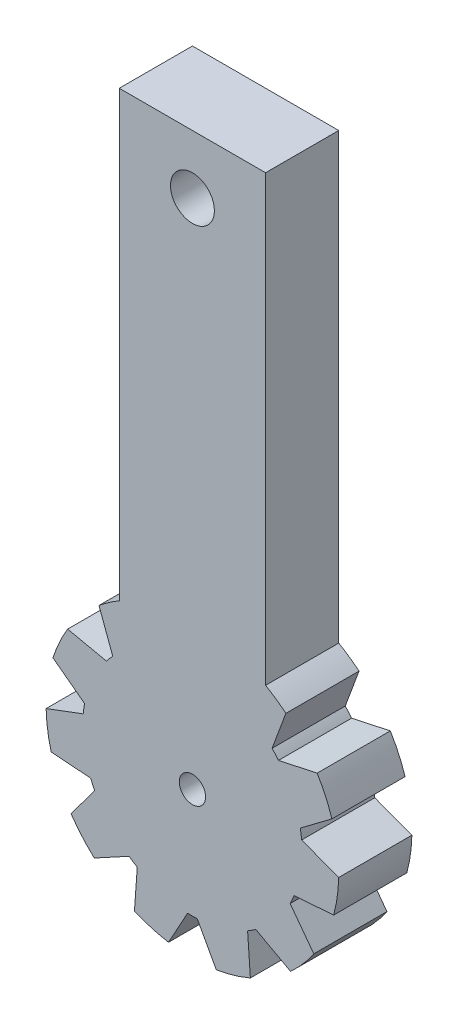
SolidWorks part; units mm, degrees
ref_plane "Front Plane" through (0, 0, 0) normal (0, 0, 1) x (1, 0, 0)
ref_plane "Top Plane" through (0, 0, 0) normal (0, 1, 0) x (1, 0, 0)
ref_plane "Right Plane" through (0, 0, 0) normal (1, 0, 0) x (0, 0, -1)
sketch "Sketch1" plane through (0, 0, 0) normal (0, 0, 1) x (1, 0, 0)
  line L0 (0, 11.2329) -> (0, -11.9005) construction
  line L1 (-1.7923, 7.2827) -> (-1.2129, 9.9262)
  line L2 (1.7923, 7.2827) -> (1.2129, 9.9262)
  line L3 (2.4295, 7.0956) -> (4.3461, 9.0062)
  line L4 (5.4451, 5.1576) -> (6.3869, 7.6947)
  line L5 (5.88, 4.6557) -> (8.5253, 5.2268)
  line L6 (7.3691, 1.395) -> (9.533, 3.0202)
  line L7 (7.4636, 0.7376) -> (9.9978, -0.2121)
  line L8 (6.9535, -2.8105) -> (9.6525, -2.6132)
  line L9 (6.6776, -3.4146) -> (8.296, -5.5836)
  line L10 (4.3302, -6.1237) -> (6.7074, -7.4169)
  line L11 (3.7715, -6.4827) -> (3.9603, -9.1824)
  line L12 (0.3321, -7.4926) -> (1.6327, -9.8658)
  line L13 (-0.3321, -7.4926) -> (-1.6327, -9.8658)
  line L14 (-3.7715, -6.4827) -> (-3.9603, -9.1824)
  line L15 (-4.3302, -6.1237) -> (-6.7074, -7.4169)
  line L16 (-6.6776, -3.4146) -> (-8.296, -5.5836)
  line L17 (-6.9535, -2.8105) -> (-9.6525, -2.6132)
  line L18 (-7.4636, 0.7376) -> (-9.9978, -0.2121)
  line L19 (-7.3691, 1.395) -> (-9.533, 3.0202)
  line L20 (-5.88, 4.6557) -> (-8.5253, 5.2268)
  line L21 (-5.4451, 5.1576) -> (-6.3869, 7.6947)
  line L22 (-2.4295, 7.0956) -> (-4.3461, 9.0062)
  arc A0 (-5.4451, 5.1576) -> (-5.88, 4.6557) centre (0, 0) ccw
  circle A1 centre (0, 0) radius 8.7846 construction
  arc A2 (1.2129, 9.9262) -> (-1.2129, 9.9262) centre (0, 0) ccw
  arc A3 (6.3869, 7.6947) -> (4.3461, 9.0062) centre (0, 0) ccw
  arc A4 (9.533, 3.0202) -> (8.5253, 5.2268) centre (0, 0) ccw
  arc A5 (9.6525, -2.6132) -> (9.9978, -0.2121) centre (0, 0) ccw
  arc A6 (6.7074, -7.4169) -> (8.296, -5.5836) centre (0, 0) ccw
  arc A7 (1.6327, -9.8658) -> (3.9603, -9.1824) centre (0, 0) ccw
  arc A8 (-3.9603, -9.1824) -> (-1.6327, -9.8658) centre (0, 0) ccw
  arc A9 (-8.296, -5.5836) -> (-6.7074, -7.4169) centre (0, 0) ccw
  arc A10 (-9.9978, -0.2121) -> (-9.6525, -2.6132) centre (0, 0) ccw
  arc A11 (-8.5253, 5.2268) -> (-9.533, 3.0202) centre (0, 0) ccw
  arc A12 (-4.3461, 9.0062) -> (-6.3869, 7.6947) centre (0, 0) ccw
  arc A13 (-7.3691, 1.395) -> (-7.4636, 0.7376) centre (0, 0) ccw
  arc A14 (2.4295, 7.0956) -> (-2.4295, 7.0956) centre (0, 0) ccw
  arc A15 (5.88, 4.6557) -> (5.4451, 5.1576) centre (0, 0) ccw
  arc A16 (7.4636, 0.7376) -> (7.3691, 1.395) centre (0, 0) ccw
  arc A17 (6.6776, -3.4146) -> (6.9535, -2.8105) centre (0, 0) ccw
  arc A18 (3.7715, -6.4827) -> (4.3302, -6.1237) centre (0, 0) ccw
  arc A19 (-0.3321, -7.4926) -> (0.3321, -7.4926) centre (0, 0) ccw
  arc A20 (-4.3302, -6.1237) -> (-3.7715, -6.4827) centre (0, 0) ccw
  arc A21 (-6.9535, -2.8105) -> (-6.6776, -3.4146) centre (0, 0) ccw
  point P54 (0, 0)
  dimension "D1" = 15
  dimension "D2" = 20
  dimension "D3" = 11
extrude "Boss-Extrude1" add sketch "Sketch1" along normal blind 5 contours A0 | A2 A0
sketch "Sketch5" plane through (0, 0, 0) normal (0, 0, -1) x (-1, 0, 0)
  circle A0 centre (0, 0) radius 2.425
  dimension "D1" = 4.85
extrude "Cut-Extrude2" cut sketch "Sketch5" against normal blind 2.7
sketch "Sketch6" plane through (0, 0, 2.7) normal (0, 0, -1) x (-1, 0, 0)
  circle A0 centre (0, 0) radius 0.9
  dimension "D1" = 1.8
extrude "Cut-Extrude3" cut sketch "Sketch6" against normal blind 12
sketch "Sketch7" plane through (0, 0, 0) normal (0, 0, -1) x (-1, 0, 0)
  line L1 (-5, 4) -> (5, 4)
  line L2 (-5, 4) -> (-5, 39)
  line L3 (-5, 39) -> (5, 39)
  line L4 (5, 4) -> (5, 39)
  point P4 (0, 4)
  dimension "D1" = 10
  dimension "D2" = 35
  dimension "D3" = 4
extrude "Boss-Extrude3" add sketch "Sketch7" against normal up to surface (5 mm away) up to face at (0.9, 0, 5)
sketch "Sketch8" plane through (0, 0, 0) normal (0, 0, -1) x (-1, 0, 0)
  circle A0 centre (0, 35) radius 1.5
  dimension "D1" = 3
  dimension "D2" = 35
extrude "Cut-Extrude4" cut sketch "Sketch8" against normal blind 12
